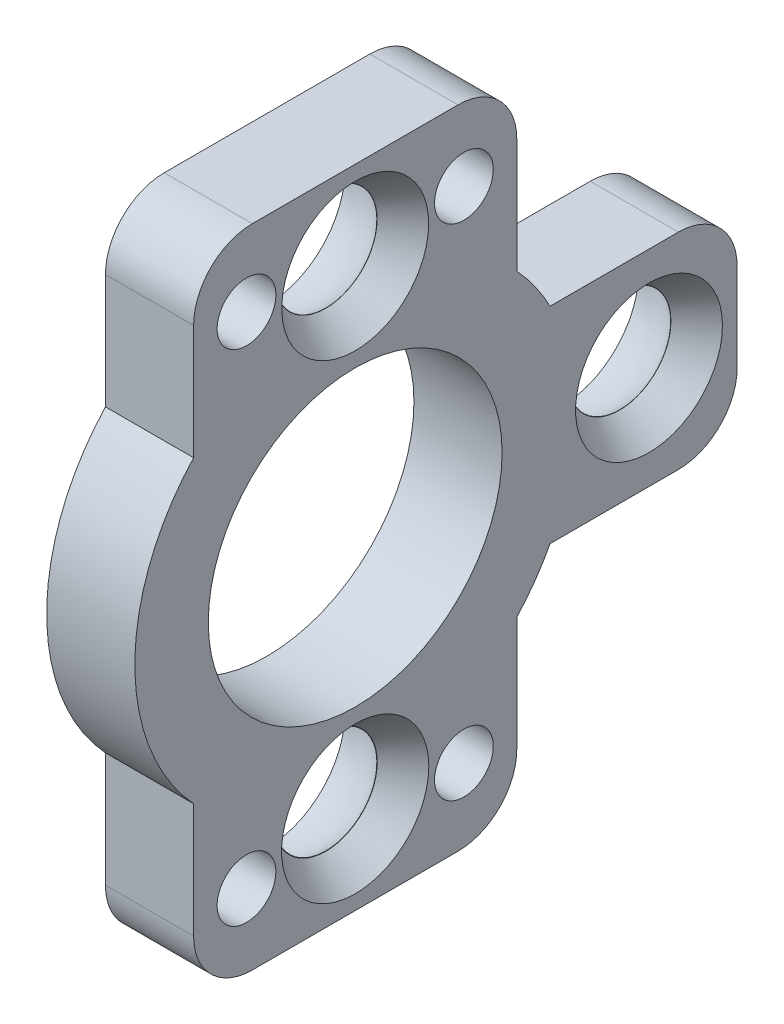
SolidWorks part; units mm, degrees
ref_plane "前视基准面" through (0, 0, 0) normal (0, 0, 1) x (1, 0, 0)
ref_plane "上视基准面" through (0, 0, 0) normal (0, 1, 0) x (1, 0, 0)
ref_plane "右视基准面" through (0, 0, 0) normal (1, 0, 0) x (0, 0, -1)
sketch "草图1" plane through (0, 0, 0) normal (1, 0, 0) x (0, 0, -1)
  circle A0 centre (0, 0) radius 5
  circle A1 centre (0, 0) radius 7.5
  dimension "D1" = 15
  dimension "D2" = 10
extrude "凸台-拉伸1" add sketch "草图1" along normal blind 3
sketch "草图2" plane through (3, 0, 0) normal (1, 0, 0) x (0, 0, -1)
  line L1 (-5.5, 11) -> (5.5, 11)
  line L2 (-5.5, 11) -> (-5.5, 5)
  line L3 (-5.5, 5) -> (5.5, 5)
  line L4 (5.5, 11) -> (5.5, 5)
  line L5 (5.5, -11) -> (-5.5, -11)
  line L6 (5.5, -11) -> (5.5, -5)
  line L7 (5.5, -5) -> (-5.5, -5)
  line L8 (-5.5, -11) -> (-5.5, -5)
  circle A0 centre (0, 0) radius 5 construction
  dimension "D1" = 11
  dimension "D2" = 6
  dimension "D3" = 5
  dimension "D4" = 5.5
  dimension "D5" = 6
  dimension "D6" = 11
  dimension "D7" = 5
  dimension "D8" = 5.5
extrude "凸台-拉伸2" add sketch "草图2" against normal blind 3
sketch "草图3" plane through (0, 0, 0) normal (-1, 0, 0) x (0, 0, 1)
  line L1 (-5.5, 11) -> (5.5, 11) construction
  line L2 (-5.5, 5.099) -> (-5.5, 11) construction
  line L3 (-2.65, 8) -> (2.65, 8)
  arc A1 (-2.65, 8) -> (2.65, 8) centre (0, 8) ccw
  dimension "D1" = 5.5
  dimension "D2" = 3
  dimension "D3" = 5.3
revolve "切除-旋转1" cut sketch "草图3" angle 360 about L3
sketch "草图4" plane through (0, 0, 0) normal (-1, 0, 0) x (0, 0, 1)
  line L0 (5.5, -11) -> (-5.5, -11) construction
  line L1 (2.65, -8) -> (-2.65, -8)
  arc A0 (-2.65, -8) -> (2.65, -8) centre (0, -8) ccw
  dimension "D1" = 5.3
  dimension "D2" = 3
revolve "切除-旋转2" cut sketch "草图4" angle 360 about L1
sketch "草图5" plane through (3, 0, 0) normal (1, 0, 0) x (0, 0, -1)
  line L0 (5.5, 11) -> (-5.5, 11) construction
  line L1 (-5.5, -5.099) -> (-5.5, -11) construction
  line L2 (-5.5, -11) -> (5.5, -11) construction
  circle A0 centre (0, 8) radius 2.5
  circle A1 centre (0, -8) radius 2.5056
  dimension "D1" = 5
  dimension "D2" = 3
  dimension "D3" = 5.5
  dimension "D4" = 3
extrude "切除-拉伸1" cut sketch "草图5" against normal blind 1 draft 37
fillet "圆角2" radius 2 4 edges at (1.5, 11, 5.5) (1.5, 11, -5.5) (1.5, -11, 5.5) (1.5, -11, -5.5)
sketch "草图7" plane through (3, 0, 0) normal (1, 0, 0) x (0, 0, -1)
  line L0 (-5.5, -5.099) -> (-5.5, -9) construction
  line L1 (-3.5, -11) -> (3.5, -11) construction
  line L2 (-7.5, 0) -> (7.5, 0) construction
  line L3 (0, -11) -> (0, 11) construction
  line L4 (3.5, 11) -> (-3.5, 11) construction
  circle A0 centre (-3.7, -8.5) radius 1
  arc A1 (-5.5, 5.099) -> (-5.5, -5.099) centre (0, 0) ccw construction
  arc A2 (5.5, -5.099) -> (5.5, 5.099) centre (0, 0) ccw construction
  circle A3 centre (3.7, -8.5) radius 1
  circle A4 centre (3.7, 8.5) radius 1
  circle A5 centre (-3.7, 8.5) radius 1
  dimension "D1" = 2
  dimension "D3" = 2.5
  dimension "D2" = 1.8
extrude "切除-拉伸3" cut sketch "草图7" against normal through all
sketch "草图8" plane through (0, 0, 0) normal (-1, 0, 0) x (0, 0, 1)
  line L1 (-5.5, 3.5) -> (-13, 3.5)
  line L2 (-5.5, 3.5) -> (-5.5, -3.5)
  line L3 (-5.5, -3.5) -> (-13, -3.5)
  line L4 (-13, 3.5) -> (-13, -3.5)
  circle A1 centre (0, 0) radius 5 construction
  point P4 (0, 0)
  point P5 (0, 0)
  point P6 (0, 0)
  dimension "D1" = 3.5
  dimension "D2" = 7
  dimension "D3" = 7.5
  dimension "D4" = 5.5
extrude "凸台-拉伸3" add sketch "草图8" against normal blind 3
sketch "草图9" plane through (0, 0, 0) normal (-1, 0, 0) x (0, 0, 1)
  line L0 (-13, 3.5) -> (-13, -3.5) construction
  line L1 (-6.6332, 3.5) -> (-13, 3.5) construction
  line L2 (-7.35, 0) -> (-12.65, 0)
  arc A0 (-7.35, 0) -> (-12.65, 0) centre (-10, 0) ccw
  dimension "D1" = 5.3
  dimension "D2" = 3
  dimension "D3" = 3.5
revolve "切除-旋转3" cut sketch "草图9" angle 360 about L2
sketch "草图10" plane through (3, 0, 0) normal (1, 0, 0) x (0, 0, -1)
  line L0 (13, -3.5) -> (6.6332, -3.5) construction
  line L2 (13, 3.5) -> (13, -3.5) construction
  circle A0 centre (10, 0) radius 2.5
  dimension "D1" = 3.5
  dimension "D2" = 3
extrude "切除-拉伸4" cut sketch "草图10" against normal blind 1 draft 37
fillet "圆角3" radius 2 2 edges at (1.5, 3.5, -13) (1.5, -3.5, -13)
